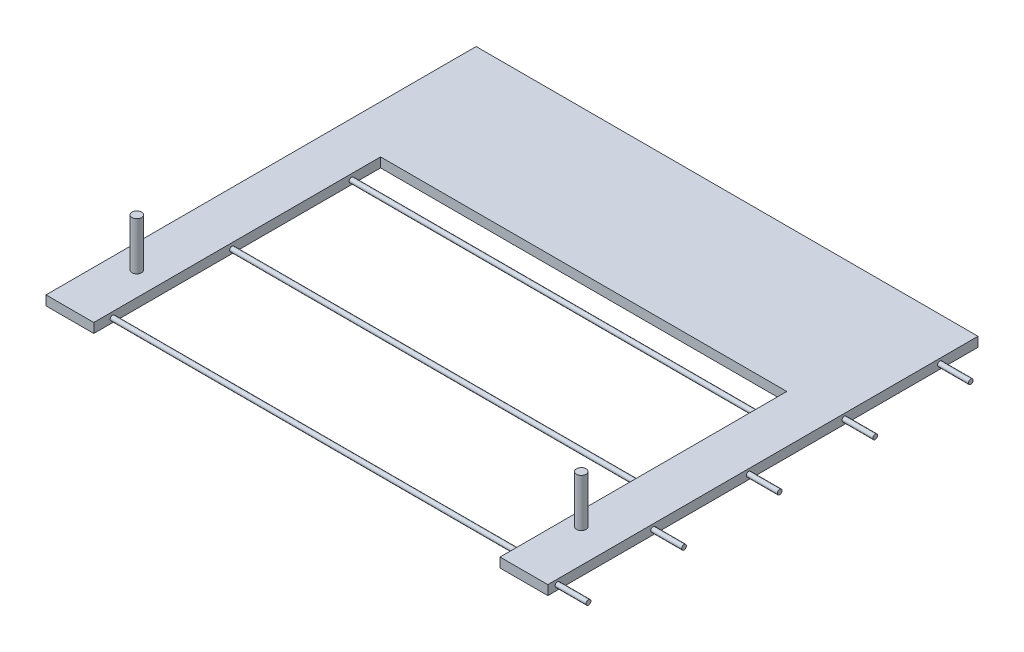
SolidWorks part; units mm, degrees
ref_plane "정면" through (0, 0, 0) normal (0, 0, 1) x (1, 0, 0)
ref_plane "윗면" through (0, 0, 0) normal (0, 1, 0) x (1, 0, 0)
ref_plane "우측면" through (0, 0, 0) normal (1, 0, 0) x (0, 0, -1)
sketch "스케치1" plane through (0, 0, 0) normal (0, 1, 0) x (1, 0, 0)
  line L1 (-52.5, 50) -> (52.5, 50)
  line L2 (-52.5, 50) -> (-52.5, -50)
  line L3 (-52.5, -50) -> (52.5, -50)
  line L4 (52.5, 50) -> (52.5, -50)
  line L5 (-52.5, 50) -> (52.5, -50) construction
  line L6 (-52.5, -50) -> (52.5, 50) construction
  point P0 (0, 0)
  dimension "D1" = 105
  dimension "D2" = 100
extrude "보스-돌출1" add sketch "스케치1" along normal blind 2
sketch "스케치2" plane through (0, 2, 0) normal (0, 1, 0) x (1, 0, 0)
  line L0 (-52.5, -50) -> (52.5, -50) construction
  line L1 (-42.5, -50) -> (42.5, -50)
  line L2 (-42.5, -50) -> (-42.5, 10)
  line L3 (-42.5, 10) -> (42.5, 10)
  line L4 (42.5, -50) -> (42.5, 10)
  line L5 (-52.5, 50) -> (-52.5, -50) construction
  line L6 (52.5, -50) -> (52.5, 50) construction
  line L7 (52.5, 50) -> (-52.5, 50) construction
  dimension "D1" = 10
  dimension "D2" = 10
  dimension "D3" = 40
extrude "컷-돌출1" cut sketch "스케치2" against normal blind 2 contours L3 L4 L1 L2
sketch "스케치4" plane through (0, 2, 0) normal (0, 1, 0) x (1, 0, 0)
  circle A0 centre (45.5, -36) radius 1
  circle A1 centre (-47.5, -36) radius 1
  dimension "D1" = 2
  dimension "D2" = 2
extrude "보스-돌출2" add sketch "스케치4" along normal blind 10
sketch "스케치5" plane through (0, 2, 0) normal (0, 1, 0) x (1, 0, 0)
  line L0 (52.5, -50) -> (52.5, 50) construction
  line L1 (-52.5, -50) -> (52.5, -50)
  line L2 (-52.5, -50) -> (-52.5, 40)
  line L3 (-52.5, 40) -> (52.5, 40)
  line L4 (52.5, -50) -> (52.5, 40)
  line L6 (-52.5, 40) -> (-52.5, 50)
  line L7 (-52.5, 50) -> (52.5, 50)
  line L8 (52.5, 50) -> (52.5, 40)
  line M8 (52.5, -50) -> (52.5, 50)
  line M9 (52.5, 50) -> (-52.5, 50)
  line M10 (-52.5, 50) -> (-52.5, -50)
  dimension "D1" = 90
extrude "컷-돌출2" cut sketch "스케치5" against normal blind 10 contours L3 M10 M8 M9
sketch "스케치7" plane through (52.5, 0, 0) normal (1, 0, 0) x (0, 0, -1)
  line L0 (-50, 2) -> (40, 2) construction
  circle A0 centre (-47.9721, 1) radius 0.5
  circle A1 centre (-27.9721, 1) radius 0.5
  circle A2 centre (-7.9721, 1) radius 0.5
  circle A3 centre (12.0279, 1) radius 0.5
  circle A4 centre (32.0279, 1) radius 0.5
  dimension "D1" = 1
  dimension "D2" = 1
  dimension "D3" = 5
extrude "보스-돌출3" add sketch "스케치7" along normal up to surface (6.4725 mm away)
sketch "스케치8" plane through (-42.5, 0, 0) normal (1, 0, 0) x (0, 0, -1)
  circle A1 centre (-46.0822, 0.8751) radius 0.5
  circle A2 centre (-21.0822, 0.8751) radius 0.5
  circle A3 centre (3.9178, 0.8751) radius 0.5
  dimension "D1" = 1
  dimension "D2" = 3
extrude "보스-돌출4" add sketch "스케치8" along normal up to surface (85 mm away) up to face at (42.5, 1, 20)
